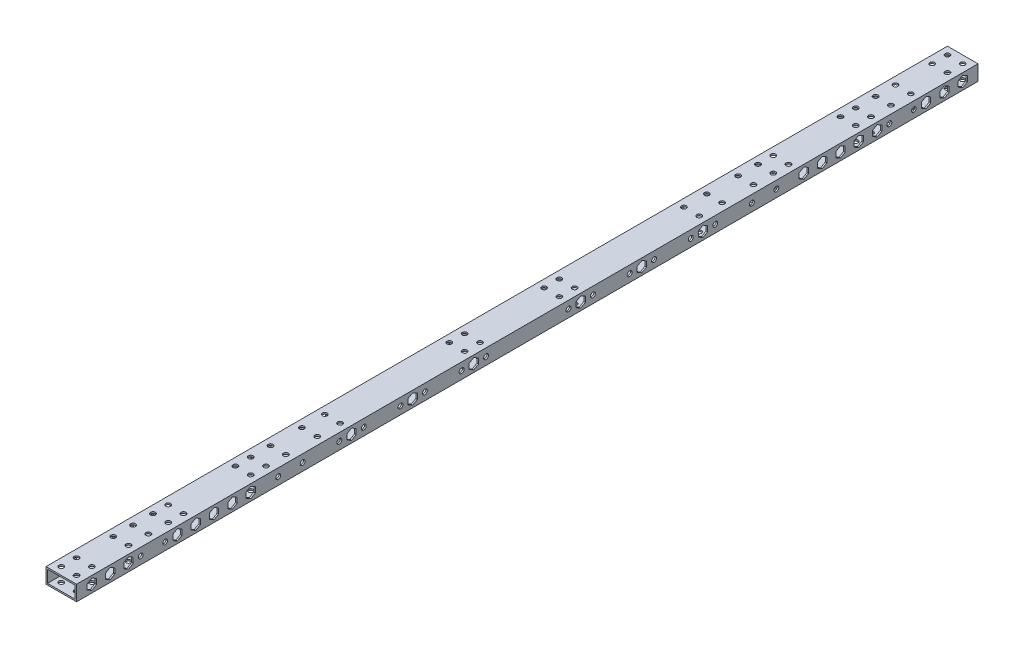
SolidWorks part; units mm, degrees
ref_plane "前视基准面" through (0, 0, 0) normal (0, 0, 1) x (1, 0, 0)
ref_plane "上视基准面" through (0, 0, 0) normal (0, 1, 0) x (1, 0, 0)
ref_plane "右视基准面" through (0, 0, 0) normal (1, 0, 0) x (0, 0, -1)
other "Configuration Table"
sketch "草图1" plane through (0, 0, 0) normal (0, 0, 1) x (1, 0, 0)
  line L1 (0, 0) -> (20, 0)
  line L2 (0, 0) -> (0, -10)
  line L3 (0, -10) -> (20, -10)
  line L4 (20, 0) -> (20, -10)
  dimension "D1" = 20
  dimension "D2" = 10
extrude "拉伸-薄壁1" add sketch "草图1" along normal blind 590 thin
sketch "草图2" plane through (0, 0, 0) normal (0, 1, 0) x (1, 0, 0)
  line L0 (0, -295) -> (20, -295) construction
  line L1 (0, -590) -> (0, 0) construction
  line L2 (20, -590) -> (20, 0) construction
  line L3 (10, 0) -> (10, -295) construction
  line L4 (20, 0) -> (0, 0) construction
  line L5 (0, -170) -> (20, -170) construction
  line L6 (0, -420) -> (20, -420) construction
  line L7 (0, -10) -> (20, -10) construction
  line L8 (0, -580) -> (20, -580) construction
  line L9 (0, -264) -> (20, -264) construction
  line L10 (0, -326) -> (20, -326) construction
  line L11 (0, -44) -> (20, -44) construction
  line L12 (0, -47) -> (20, -47) construction
  line L13 (20, -45.5) -> (0, -45.5) construction
  line L14 (0, -147) -> (20, -147) construction
  line L15 (0, -70) -> (20, -70) construction
  line L16 (20, -97) -> (0, -97) construction
  line L17 (0, -124) -> (20, -124) construction
  line L18 (0, -466) -> (20, -466) construction
  line L19 (20, -493) -> (0, -493) construction
  line L20 (0, -520) -> (20, -520) construction
  line L21 (20, -544.5) -> (0, -544.5) construction
  line L22 (0, -543) -> (20, -543) construction
  line L23 (0, -546) -> (20, -546) construction
  circle A0 centre (5, -162.5) radius 1.575
  circle A1 centre (15, -162.5) radius 1.575
  circle A2 centre (15, -177.5) radius 1.575
  circle A3 centre (5, -177.5) radius 1.575
  circle A4 centre (5, -412.5) radius 1.575
  circle A5 centre (15, -412.5) radius 1.575
  circle A6 centre (15, -427.5) radius 1.575
  circle A7 centre (5, -427.5) radius 1.575
  circle A12 centre (5, -5) radius 1.575
  circle A13 centre (15, -5) radius 1.575
  circle A14 centre (15, -15) radius 1.575
  circle A15 centre (5, -15) radius 1.575
  circle A16 centre (5, -575) radius 1.575
  circle A17 centre (15, -575) radius 1.575
  circle A18 centre (15, -585) radius 1.575
  circle A19 centre (5, -585) radius 1.575
  circle A20 centre (5, -259) radius 1.575
  circle A21 centre (15, -259) radius 1.575
  circle A22 centre (15, -269) radius 1.575
  circle A23 centre (5, -269) radius 1.575
  circle A24 centre (5, -321) radius 1.575
  circle A25 centre (15, -321) radius 1.575
  circle A26 centre (15, -331) radius 1.575
  circle A27 centre (5, -331) radius 1.575
  circle A28 centre (15, -39) radius 1.6
  circle A29 centre (5, -39) radius 1.6
  circle A30 centre (5, -52) radius 1.6
  circle A31 centre (15, -52) radius 1.6
  circle A32 centre (15, -142) radius 1.6
  circle A33 centre (5, -142) radius 1.6
  circle A34 centre (5, -65) radius 1.6
  circle A35 centre (15, -65) radius 1.6
  circle A36 centre (15, -75) radius 1.6
  circle A37 centre (5, -75) radius 1.6
  circle A38 centre (5, -119) radius 1.6
  circle A39 centre (15, -119) radius 1.6
  circle A40 centre (15, -129) radius 1.6
  circle A41 centre (5, -129) radius 1.6
  circle A42 centre (5, -461) radius 1.6
  circle A43 centre (15, -461) radius 1.6
  circle A44 centre (15, -471) radius 1.6
  circle A45 centre (5, -471) radius 1.6
  circle A46 centre (5, -515) radius 1.6
  circle A47 centre (15, -515) radius 1.6
  circle A48 centre (15, -525) radius 1.6
  circle A49 centre (5, -525) radius 1.6
  circle A50 centre (5, -448) radius 1.6
  circle A51 centre (15, -448) radius 1.6
  circle A52 centre (15, -538) radius 1.6
  circle A53 centre (5, -538) radius 1.6
  circle A54 centre (5, -551) radius 1.6
  circle A55 centre (15, -551) radius 1.6
  dimension "D1" = 3.15
  dimension "D5" = 10
  dimension "D6" = 5
  dimension "D8" = 3.15
  dimension "D9" = 3.15
  dimension "D15" = 3.2
  dimension "D20" = 3.2
  dimension "D24" = 3.2
  dimension "D2" = 7.5
  dimension "D3" = 5
  dimension "D4" = 125
  dimension "D7" = 5
  dimension "D10" = 31
  dimension "D11" = 5
  dimension "D12" = 5
  dimension "D13" = 44
  dimension "D14" = 3
  dimension "D16" = 5
  dimension "D17" = 5
  dimension "D18" = 1.5
  dimension "D19" = 100
  dimension "D21" = 5
  dimension "D22" = 5
  dimension "D23" = 70
  dimension "D25" = 5
  dimension "D26" = 5
  dimension "D27" = 50
extrude "切除-拉伸1" cut sketch "草图2" against normal through all
sketch "草图3" plane through (0, 0, 0) normal (-1, 0, 0) x (0, 0, 1)
  line L0 (540, 0) -> (540, -10) construction
  line L1 (590, 0) -> (0, 0) construction
  line L2 (590, -10) -> (0, -10) construction
  line L3 (590, 0) -> (590, -10) construction
  line L4 (590, -5) -> (0, -5) construction
  line L5 (0, 0) -> (0, -10) construction
  line L6 (450, 0) -> (450, -10) construction
  line L7 (295, 0) -> (295, -10) construction
  line L8 (140, 0) -> (140, -10) construction
  line L9 (50, 0) -> (50, -10) construction
  line L10 (22, -1.5) -> (18.9689, -3.25)
  line L11 (10, -1.5) -> (6.9689, -3.25)
  line L12 (6.9689, -3.25) -> (6.9689, -6.75)
  line L13 (6.9689, -6.75) -> (10, -8.5)
  line L14 (10, -8.5) -> (13.0311, -6.75)
  line L15 (13.0311, -6.75) -> (13.0311, -3.25)
  line L16 (13.0311, -3.25) -> (10, -1.5)
  line L17 (25.0311, -3.25) -> (22, -1.5)
  line L18 (25.0311, -6.75) -> (25.0311, -3.25)
  line L19 (18.9689, -6.75) -> (22, -8.5)
  line L20 (18.9689, -3.25) -> (18.9689, -6.75)
  line L21 (22, -8.5) -> (25.0311, -6.75)
  line L22 (34, -1.5) -> (30.9689, -3.25)
  line L23 (37.0311, -3.25) -> (34, -1.5)
  line L24 (37.0311, -6.75) -> (37.0311, -3.25)
  line L25 (30.9689, -6.75) -> (34, -8.5)
  line L26 (30.9689, -3.25) -> (30.9689, -6.75)
  line L27 (34, -8.5) -> (37.0311, -6.75)
  line L28 (66, -8.5) -> (62.9689, -6.75)
  line L29 (69.0311, -3.25) -> (69.0311, -6.75)
  line L30 (69.0311, -6.75) -> (66, -8.5)
  line L31 (62.9689, -6.75) -> (62.9689, -3.25)
  line L32 (62.9689, -3.25) -> (66, -1.5)
  line L33 (66, -1.5) -> (69.0311, -3.25)
  line L34 (78, -8.5) -> (74.9689, -6.75)
  line L35 (81.0311, -3.25) -> (81.0311, -6.75)
  line L36 (81.0311, -6.75) -> (78, -8.5)
  line L37 (74.9689, -6.75) -> (74.9689, -3.25)
  line L38 (74.9689, -3.25) -> (78, -1.5)
  line L39 (86.9689, -3.25) -> (90, -1.5)
  line L40 (86.9689, -6.75) -> (86.9689, -3.25)
  line L41 (90, -8.5) -> (86.9689, -6.75)
  line L42 (93.0311, -6.75) -> (90, -8.5)
  line L43 (93.0311, -3.25) -> (93.0311, -6.75)
  line L44 (90, -1.5) -> (93.0311, -3.25)
  line L45 (78, -1.5) -> (81.0311, -3.25)
  line L46 (98.9689, -3.25) -> (102, -1.5)
  line L47 (102, -1.5) -> (105.0311, -3.25)
  line L48 (105.0311, -3.25) -> (105.0311, -6.75)
  line L49 (105.0311, -6.75) -> (102, -8.5)
  line L50 (102, -8.5) -> (98.9689, -6.75)
  line L51 (98.9689, -6.75) -> (98.9689, -3.25)
  line L52 (110.9689, -3.25) -> (114, -1.5)
  line L53 (114, -1.5) -> (117.0311, -3.25)
  line L54 (117.0311, -3.25) -> (117.0311, -6.75)
  line L55 (117.0311, -6.75) -> (114, -8.5)
  line L56 (114, -8.5) -> (110.9689, -6.75)
  line L57 (110.9689, -6.75) -> (110.9689, -3.25)
  line L58 (479.0311, -6.75) -> (479.0311, -3.25)
  line L59 (476, -8.5) -> (479.0311, -6.75)
  line L60 (472.9689, -6.75) -> (476, -8.5)
  line L61 (472.9689, -3.25) -> (472.9689, -6.75)
  line L62 (476, -1.5) -> (472.9689, -3.25)
  line L63 (479.0311, -3.25) -> (476, -1.5)
  line L64 (491.0311, -6.75) -> (491.0311, -3.25)
  line L65 (488, -8.5) -> (491.0311, -6.75)
  line L66 (484.9689, -6.75) -> (488, -8.5)
  line L67 (484.9689, -3.25) -> (484.9689, -6.75)
  line L68 (488, -1.5) -> (484.9689, -3.25)
  line L69 (491.0311, -3.25) -> (488, -1.5)
  line L70 (512, -1.5) -> (508.9689, -3.25)
  line L71 (500, -1.5) -> (496.9689, -3.25)
  line L72 (496.9689, -3.25) -> (496.9689, -6.75)
  line L73 (496.9689, -6.75) -> (500, -8.5)
  line L74 (500, -8.5) -> (503.0311, -6.75)
  line L75 (503.0311, -6.75) -> (503.0311, -3.25)
  line L76 (503.0311, -3.25) -> (500, -1.5)
  line L77 (515.0311, -3.25) -> (512, -1.5)
  line L78 (515.0311, -6.75) -> (515.0311, -3.25)
  line L79 (508.9689, -6.75) -> (512, -8.5)
  line L80 (508.9689, -3.25) -> (508.9689, -6.75)
  line L81 (512, -8.5) -> (515.0311, -6.75)
  line L82 (524, -1.5) -> (520.9689, -3.25)
  line L83 (527.0311, -3.25) -> (524, -1.5)
  line L84 (527.0311, -6.75) -> (527.0311, -3.25)
  line L85 (520.9689, -6.75) -> (524, -8.5)
  line L86 (520.9689, -3.25) -> (520.9689, -6.75)
  line L87 (524, -8.5) -> (527.0311, -6.75)
  line L88 (556, -8.5) -> (552.9689, -6.75)
  line L89 (559.0311, -3.25) -> (559.0311, -6.75)
  line L90 (559.0311, -6.75) -> (556, -8.5)
  line L91 (552.9689, -6.75) -> (552.9689, -3.25)
  line L92 (552.9689, -3.25) -> (556, -1.5)
  line L93 (556, -1.5) -> (559.0311, -3.25)
  line L94 (568, -8.5) -> (564.9689, -6.75)
  line L95 (571.0311, -3.25) -> (571.0311, -6.75)
  line L96 (571.0311, -6.75) -> (568, -8.5)
  line L97 (564.9689, -6.75) -> (564.9689, -3.25)
  line L98 (564.9689, -3.25) -> (568, -1.5)
  line L99 (576.9689, -3.25) -> (580, -1.5)
  line L100 (576.9689, -6.75) -> (576.9689, -3.25)
  line L101 (580, -8.5) -> (576.9689, -6.75)
  line L102 (583.0311, -6.75) -> (580, -8.5)
  line L103 (583.0311, -3.25) -> (583.0311, -6.75)
  line L104 (580, -1.5) -> (583.0311, -3.25)
  line L105 (568, -1.5) -> (571.0311, -3.25)
  line L106 (220, -1.5) -> (216.9689, -3.25)
  line L107 (180, -1.5) -> (176.9689, -3.25)
  line L108 (176.9689, -3.25) -> (176.9689, -6.75)
  line L109 (176.9689, -6.75) -> (180, -8.5)
  line L110 (180, -8.5) -> (183.0311, -6.75)
  line L111 (183.0311, -6.75) -> (183.0311, -3.25)
  line L112 (183.0311, -3.25) -> (180, -1.5)
  line L113 (223.0311, -3.25) -> (220, -1.5)
  line L114 (223.0311, -6.75) -> (223.0311, -3.25)
  line L115 (220, -8.5) -> (223.0311, -6.75)
  line L116 (216.9689, -6.75) -> (220, -8.5)
  line L117 (216.9689, -3.25) -> (216.9689, -6.75)
  line L118 (260, -1.5) -> (256.9689, -3.25)
  line L119 (263.0311, -3.25) -> (260, -1.5)
  line L120 (263.0311, -6.75) -> (263.0311, -3.25)
  line L121 (260, -8.5) -> (263.0311, -6.75)
  line L122 (256.9689, -6.75) -> (260, -8.5)
  line L123 (256.9689, -3.25) -> (256.9689, -6.75)
  line L124 (406.9689, -3.25) -> (410, -1.5)
  line L125 (406.9689, -6.75) -> (406.9689, -3.25)
  line L126 (410, -8.5) -> (406.9689, -6.75)
  line L127 (413.0311, -6.75) -> (410, -8.5)
  line L128 (413.0311, -3.25) -> (413.0311, -6.75)
  line L129 (410, -1.5) -> (413.0311, -3.25)
  line L130 (333.0311, -3.25) -> (333.0311, -6.75)
  line L131 (333.0311, -6.75) -> (330, -8.5)
  line L132 (330, -8.5) -> (326.9689, -6.75)
  line L133 (326.9689, -6.75) -> (326.9689, -3.25)
  line L134 (326.9689, -3.25) -> (330, -1.5)
  line L135 (330, -1.5) -> (333.0311, -3.25)
  line L136 (373.0311, -3.25) -> (373.0311, -6.75)
  line L137 (373.0311, -6.75) -> (370, -8.5)
  line L138 (370, -8.5) -> (366.9689, -6.75)
  line L139 (366.9689, -6.75) -> (366.9689, -3.25)
  line L140 (366.9689, -3.25) -> (370, -1.5)
  line L141 (370, -1.5) -> (373.0311, -3.25)
  circle A0 centre (548, -5) radius 1.575
  circle A1 centre (532, -5) radius 1.575
  circle A2 centre (458, -5) radius 1.6
  circle A3 centre (442, -5) radius 1.6
  circle A4 centre (148, -5) radius 1.6
  circle A5 centre (132, -5) radius 1.6
  circle A6 centre (58, -5) radius 1.575
  circle A7 centre (42, -5) radius 1.575
  circle A8 centre (402, -5) radius 1.6
  circle A9 centre (418, -5) radius 1.6
  circle A10 centre (362, -5) radius 1.6
  circle A11 centre (378, -5) radius 1.6
  circle A12 centre (322, -5) radius 1.6
  circle A13 centre (338, -5) radius 1.6
  circle A14 centre (252, -5) radius 1.6
  circle A15 centre (268, -5) radius 1.6
  circle A16 centre (212, -5) radius 1.6
  circle A17 centre (228, -5) radius 1.6
  circle A18 centre (172, -5) radius 1.6
  circle A19 centre (188, -5) radius 1.6
  circle A20 centre (10, -5) radius 3.0311 construction
  circle A21 centre (22, -5) radius 3.0311 construction
  circle A22 centre (34, -5) radius 3.0311 construction
  circle A23 centre (66, -5) radius 3.0311 construction
  circle A24 centre (78, -5) radius 3.0311 construction
  circle A25 centre (90, -5) radius 3.0311 construction
  circle A26 centre (102, -5) radius 3.0311 construction
  circle A27 centre (114, -5) radius 3.0311 construction
  circle A28 centre (476, -5) radius 3.0311 construction
  circle A29 centre (488, -5) radius 3.0311 construction
  circle A30 centre (500, -5) radius 3.0311 construction
  circle A31 centre (512, -5) radius 3.0311 construction
  circle A32 centre (524, -5) radius 3.0311 construction
  circle A33 centre (556, -5) radius 3.0311 construction
  circle A34 centre (568, -5) radius 3.0311 construction
  circle A35 centre (580, -5) radius 3.0311 construction
  circle A36 centre (180, -5) radius 3.0311 construction
  circle A37 centre (220, -5) radius 3.0311 construction
  circle A38 centre (260, -5) radius 3.0311 construction
  circle A39 centre (330, -5) radius 3.0311 construction
  circle A40 centre (370, -5) radius 3.0311 construction
  point P14 (540, -5)
  dimension "D2" = 3.15
  dimension "D5" = 3.2
  dimension "D1" = 50
  dimension "D3" = 8
  dimension "D4" = 140
  dimension "D6" = 8
  dimension "D7" = 40
  dimension "D8" = 3.5
  dimension "D9" = 10
  dimension "D11" = 12
  dimension "D13" = 12
  dimension "D14" = 3.5
  dimension "D15" = 8
  dimension "D16" = 40
  dimension "D10" = 3
  dimension "D12" = 3
extrude "切除-拉伸2" cut sketch "草图3" against normal through all and the other way through all
